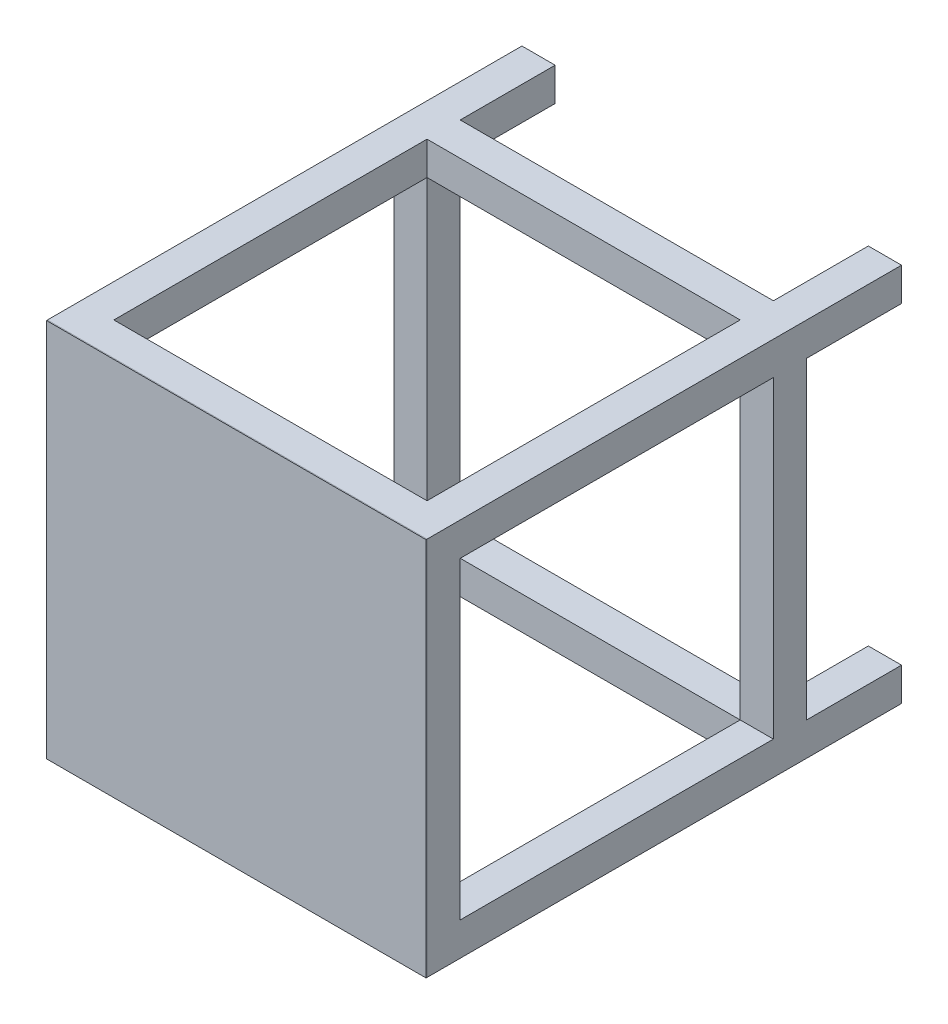
SolidWorks part; units mm, degrees
ref_plane "Plan de face" through (0, 0, 0) normal (0, 0, 1) x (1, 0, 0)
ref_plane "Plan de dessus" through (0, 0, 0) normal (0, 1, 0) x (1, 0, 0)
ref_plane "Plan de droite" through (0, 0, 0) normal (1, 0, 0) x (0, 0, -1)
sketch "Esquisse1" plane through (0, 0, 0) normal (0, 0, 1) x (1, 0, 0)
  line L1 (0, 0) -> (400, 0)
  line L2 (0, 0) -> (0, -400)
  line L3 (0, -400) -> (400, -400)
  line L4 (400, 0) -> (400, -400)
  dimension "D1" = 400
  dimension "D2" = 400
extrude "Extru.-Mince1" add sketch "Esquisse1" along normal blind 35 thin
sketch "Esquisse2" plane through (0, 0, 0) normal (0, 0, -1) x (-1, 0, 0)
  line L0 (-35, -365) -> (-365, -365) construction
  line L1 (-365, -35) -> (-400, -35)
  line L2 (-365, -35) -> (-365, 0)
  line L3 (-365, 0) -> (-400, 0)
  line L4 (-400, -35) -> (-400, 0)
  line L5 (0, 0) -> (-35, 0)
  line L6 (0, 0) -> (0, -35)
  line L7 (0, -35) -> (-35, -35)
  line L8 (-35, 0) -> (-35, -35)
  line L9 (-35, -365) -> (0, -365)
  line L10 (-35, -365) -> (-35, -400)
  line L11 (-35, -400) -> (0, -400)
  line L12 (0, -365) -> (0, -400)
  line L13 (-365, -365) -> (-400, -365)
  line L14 (-365, -365) -> (-365, -400)
  line L15 (-365, -400) -> (-400, -400)
  line L16 (-400, -365) -> (-400, -400)
extrude "Boss.-Extru.1" add sketch "Esquisse2" along normal blind 465
sketch "Esquisse3" plane through (0, 0, 35) normal (0, 0, 1) x (1, 0, 0)
  line L1 (0, 0) -> (400, 0)
  line L2 (0, 0) -> (0, -400)
  line L3 (0, -400) -> (400, -400)
  line L4 (400, 0) -> (400, -400)
extrude "Boss.-Extru.2" add sketch "Esquisse3" along normal blind 1 separate body
sketch "Esquisse4" plane through (35, 0, 0) normal (1, 0, 0) x (0, 0, -1)
  line L0 (465, -35) -> (0, -35) construction
  line L1 (330, -35) -> (365, -35)
  line L2 (330, -35) -> (330, 0)
  line L3 (330, 0) -> (365, 0)
  line L4 (365, -35) -> (365, 0)
  line L5 (465, 0) -> (0, 0) construction
  line L6 (465, -400) -> (0, -400) construction
  line L7 (330, -400) -> (365, -400)
  line L8 (330, -400) -> (330, -365)
  line L9 (330, -365) -> (365, -365)
  line L10 (365, -400) -> (365, -365)
  line L11 (465, -365) -> (0, -365) construction
  line L12 (465, 0) -> (465, -35) construction
  line L13 (465, -365) -> (465, -400) construction
  dimension "D1" = 35
  dimension "D2" = 35
  dimension "D3" = 100
  dimension "D4" = 100
extrude "Boss.-Extru.3" add sketch "Esquisse4" along normal up to surface (330 mm away) up to face at (365, -17.5, -232.5)
sketch "Esquisse5" plane through (0, -365, 0) normal (0, 1, 0) x (1, 0, 0)
  line L0 (0, 465) -> (0, 0) construction
  line L1 (35, 330) -> (0, 330)
  line L2 (35, 330) -> (35, 365)
  line L3 (35, 365) -> (0, 365)
  line L4 (0, 330) -> (0, 365)
  line L5 (400, 465) -> (400, 0) construction
  line L6 (365, 330) -> (400, 330)
  line L7 (365, 330) -> (365, 365)
  line L8 (365, 365) -> (400, 365)
  line L9 (400, 330) -> (400, 365)
extrude "Boss.-Extru.4" add sketch "Esquisse5" along normal up to surface (330 mm away) up to face at (200, -35, -270.8333)
